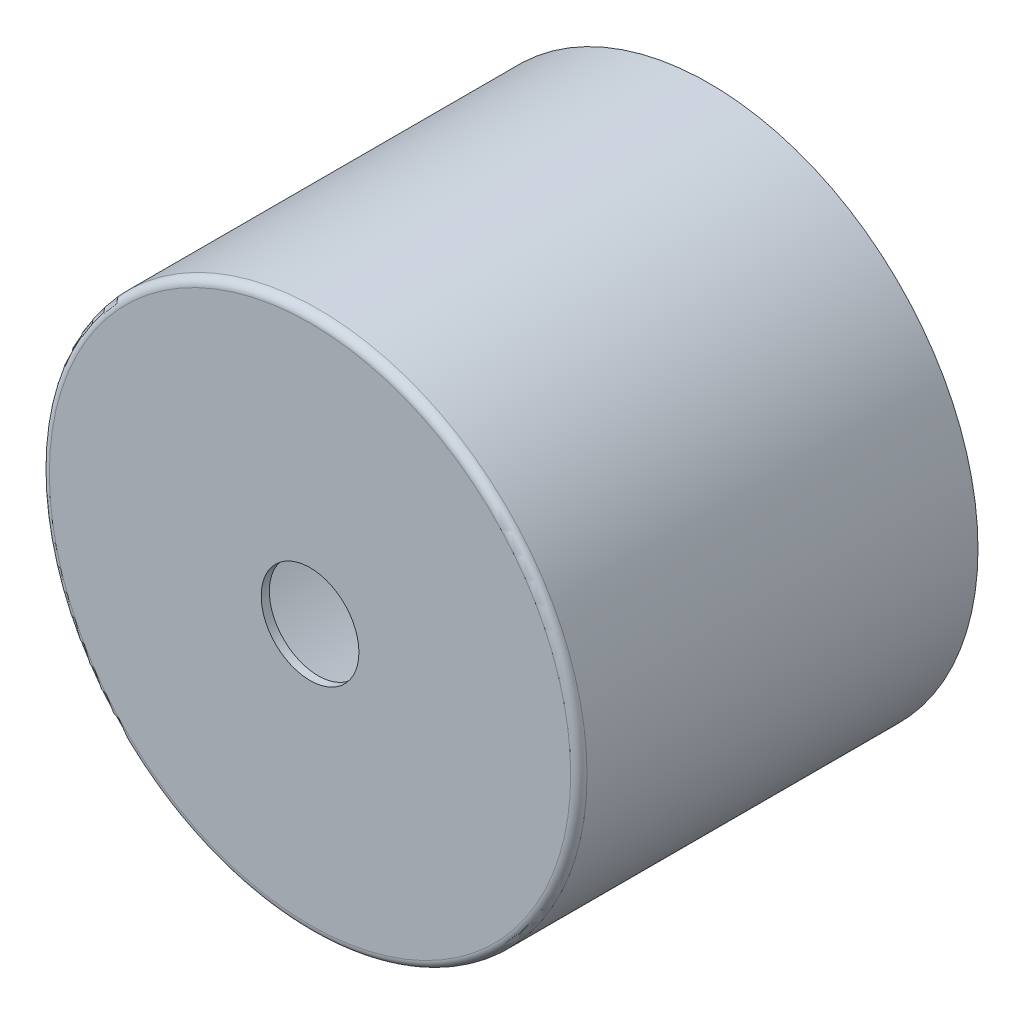
SolidWorks part; units mm, degrees
ref_plane "Front Plane" through (0, 0, 0) normal (0, 0, 1) x (1, 0, 0)
ref_plane "Top Plane" through (0, 0, 0) normal (0, 1, 0) x (1, 0, 0)
ref_plane "Right Plane" through (0, 0, 0) normal (1, 0, 0) x (0, 0, -1)
sketch "Sketch1" plane through (0, 0, 0) normal (0, 0, 1) x (1, 0, 0)
  circle A0 centre (0, 0) radius 16.5
  dimension "D1" = 33
extrude "Boss-Extrude1" add sketch "Sketch1" against normal blind 24.5
shell "Shell1" thickness 0.5
sketch "Sketch2" plane through (0, 0, 0) normal (0, 0, 1) x (1, 0, 0)
  circle A0 centre (0, 0) radius 3
  dimension "D1" = 6
extrude "Cut-Extrude1" cut sketch "Sketch2" against normal through all
fillet "Fillet1" radius 0.5 1 edges at (16.5, 0, 0)
